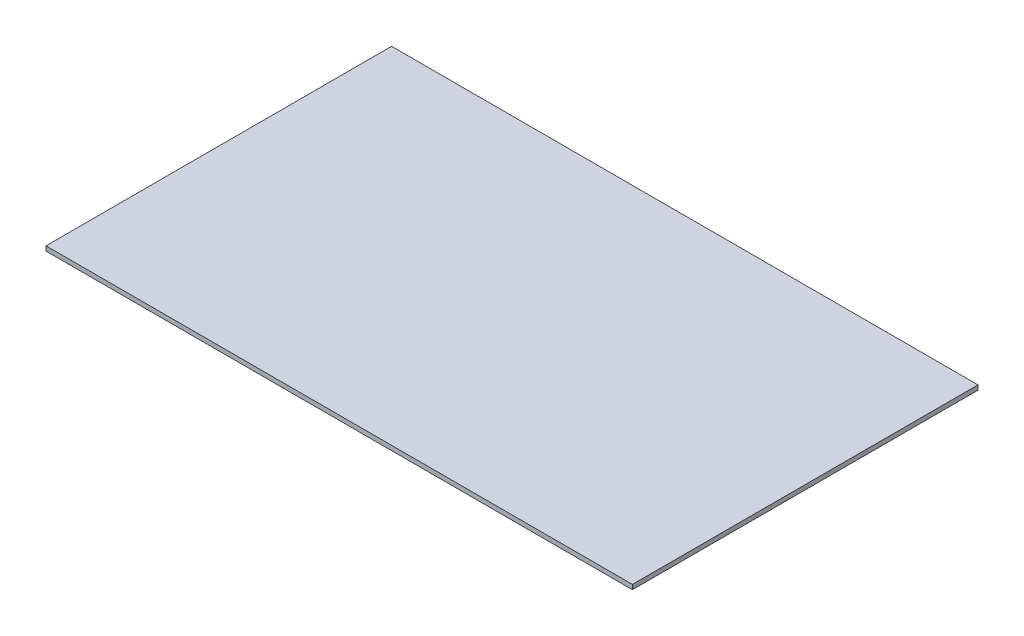
SolidWorks part; units mm, degrees
material "Pine"
ref_plane "Front Plane" through (0, 0, 0) normal (0, 0, 1) x (1, 0, 0)
ref_plane "Top Plane" through (0, 0, 0) normal (0, 1, 0) x (1, 0, 0)
ref_plane "Right Plane" through (0, 0, 0) normal (1, 0, 0) x (0, 0, -1)
sketch "Sketch1" plane through (0, 0, 0) normal (0, 1, 0) x (1, 0, 0)
  line L1 (-355.6, -209.55) -> (355.6, -209.55)
  line L2 (-355.6, -209.55) -> (-355.6, 209.55)
  line L3 (-355.6, 209.55) -> (355.6, 209.55)
  line L4 (355.6, -209.55) -> (355.6, 209.55)
  line L5 (-355.6, -209.55) -> (355.6, 209.55) construction
  line L6 (-355.6, 209.55) -> (355.6, -209.55) construction
  point P0 (0, 0)
  dimension "D1" = 711.2
  dimension "D2" = 419.1
extrude "Boss-Extrude1" add sketch "Sketch1" along normal blind 5.5562
